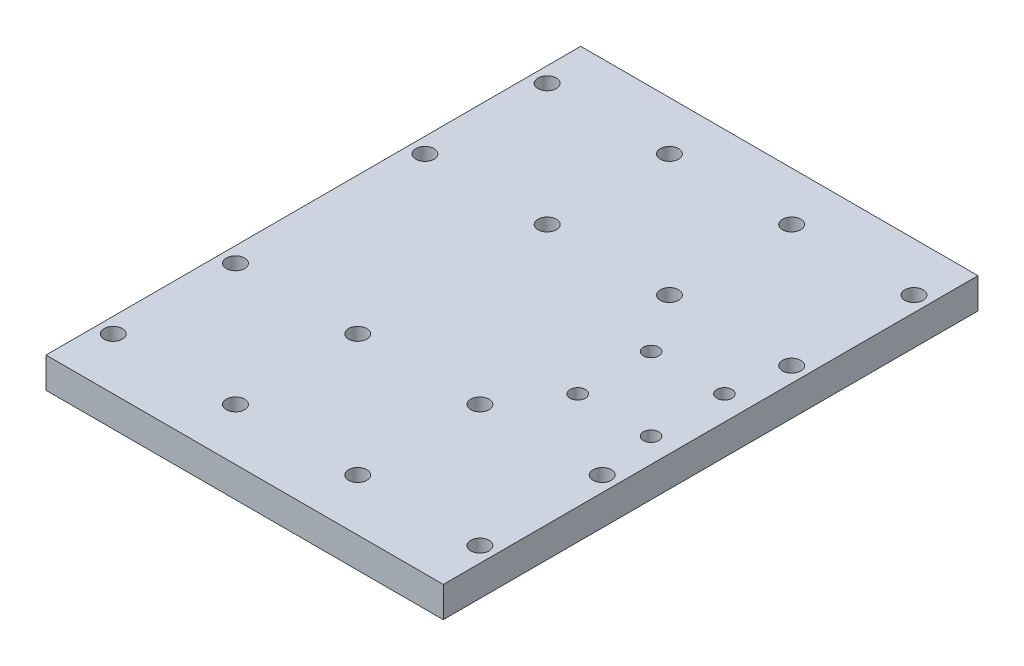
SolidWorks part; units mm, degrees
ref_plane "Front Plane" through (0, 0, 0) normal (0, 0, 1) x (1, 0, 0)
ref_plane "Top Plane" through (0, 0, 0) normal (0, 1, 0) x (1, 0, 0)
ref_plane "Right Plane" through (0, 0, 0) normal (1, 0, 0) x (0, 0, -1)
sketch "Sketch1" plane through (0, 0, 0) normal (0, 1, 0) x (1, 0, 0)
  line L0 (0, 34.4931) -> (5, 34.4931)
  line L1 (0, 34.4931) -> (0, -121.5069)
  line L2 (0, -121.5069) -> (130, -121.5069)
  line L3 (0, 34.4931) -> (130, 34.4931)
  line L4 (130, -121.5069) -> (130, 34.4931)
  line L5 (5, 34.4931) -> (5, 27.4931)
  line L11 (45, -74.5069) -> (45, -114.5069)
  line L19 (125, -74.5069) -> (125, -114.5069)
  circle A0 centre (5, 27.4931) radius 3
  circle A1 centre (45, 27.4931) radius 3
  circle A2 centre (45, -12.5069) radius 3
  circle A3 centre (5, -12.5069) radius 3
  circle A4 centre (85, 27.4931) radius 3
  circle A5 centre (125, 27.4931) radius 3
  circle A6 centre (85, -12.5069) radius 3
  circle A7 centre (125, -12.5069) radius 3
  circle A8 centre (85, -74.5069) radius 3
  circle A9 centre (125, -74.5069) radius 3
  circle A10 centre (125, -114.5069) radius 3
  circle A11 centre (85, -114.5069) radius 3
  circle A12 centre (5, -74.5069) radius 3
  circle A13 centre (45, -74.5069) radius 3
  circle A14 centre (5, -114.5069) radius 3
  circle A15 centre (45, -114.5069) radius 3
extrude "Boss-Extrude1" add sketch "Sketch1" along normal blind 10
sketch "Sketch2" plane through (0, 10, 0) normal (0, 1, 0) x (1, 0, 0)
  circle A0 centre (98, -31.5069) radius 2.5
  circle A1 centre (98, -55.5069) radius 2.5
  circle A2 centre (122, -55.5069) radius 2.5
  circle A3 centre (122, -31.5069) radius 2.5
extrude "Cut-Extrude1" cut sketch "Sketch2" against normal blind 10
sketch "Sketch3" plane through (0, 0, -34.4931) normal (0, 0, -1) x (-1, 0, 0)
  line L1 (0, 10) -> (-130, 10)
  line L2 (0, 10) -> (0, 0)
  line L3 (0, 0) -> (-130, 0)
  line L4 (-130, 10) -> (-130, 0)
extrude "Boss-Extrude2" add sketch "Sketch3" along normal blind 10
sketch "Sketch4" plane through (0, 0, -44.4931) normal (0, 0, -1) x (-1, 0, 0)
  line L1 (0, 10) -> (-130, 10)
  line L2 (0, 10) -> (0, 0)
  line L3 (0, 0) -> (-130, 0)
  line L4 (-130, 10) -> (-130, 0)
extrude "Cut-Extrude2" cut sketch "Sketch4" against normal blind 10
sketch "Sketch5" plane through (0, 0, 121.5069) normal (0, 0, 1) x (1, 0, 0)
  line L1 (0, 0) -> (130, 0)
  line L2 (0, 0) -> (0, 10)
  line L3 (0, 10) -> (130, 10)
  line L4 (130, 0) -> (130, 10)
extrude "Boss-Extrude3" add sketch "Sketch5" along normal blind 10
sketch "Sketch6" plane through (0, 0, -34.4931) normal (0, 0, -1) x (-1, 0, 0)
  line L1 (0, 10) -> (-130, 10)
  line L2 (0, 10) -> (0, 0)
  line L3 (0, 0) -> (-130, 0)
  line L4 (-130, 10) -> (-130, 0)
extrude "Boss-Extrude4" add sketch "Sketch6" along normal blind 8.98
